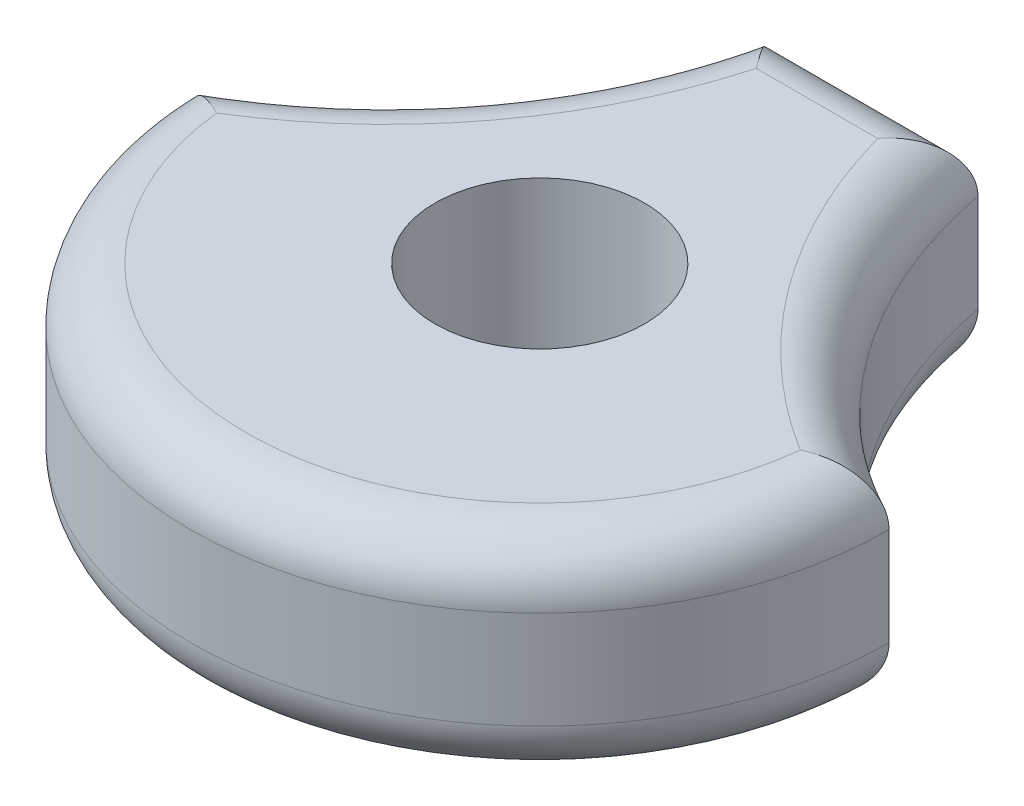
SolidWorks part; units mm, degrees
ref_plane "Front Plane" through (0, 0, 0) normal (0, 0, 1) x (1, 0, 0)
ref_plane "Top Plane" through (0, 0, 0) normal (0, 1, 0) x (1, 0, 0)
ref_plane "Right Plane" through (0, 0, 0) normal (1, 0, 0) x (0, 0, -1)
sketch "Sketch1" plane through (0, 0, 0) normal (0, 1, 0) x (1, 0, 0)
  line L1 (-0.188, 0.5961) -> (0.188, 0.5961)
  arc A0 (-0.625, 0) -> (0.625, 0) centre (0, 0) ccw
  arc A3 (-0.625, 0) -> (-0.188, 0.5961) centre (-1.0238, 0.7506) ccw
  arc A4 (0.188, 0.5961) -> (0.625, 0) centre (1.0238, 0.7506) ccw
  point P1 (0, 0)
  point P8 (0, 0)
  point P13 (0, 0)
  point P14 (-1.0193, 0.7513)
  point P15 (-1.6845, 0.7083)
  point P16 (0, 0)
  point P17 (0, 0)
  point P18 (0, 0)
  point P19 (1.0238, 0.7506)
  dimension "D1" = 1.25
  dimension "D3" = 0.376
extrude "Boss-Extrude1" add sketch "Sketch1" along normal blind 0.375
sketch "Sketch2" plane through (0, 0.375, 0) normal (0, 1, 0) x (1, 0, 0)
  circle A0 centre (0, 0) radius 0.1875
  dimension "D1" = 0.375
extrude "Cut-Extrude1" cut sketch "Sketch2" against normal blind 0.375
fillet "Fillet2" radius 0.1 8 edges at (0, 0, 0.625) (0.3383, 0, -0.248) (0, 0, -0.5961) (-0.3383, 0, -0.248) (-0.3383, 0.375, -0.248) (0, 0.375, -0.5961) (0.3383, 0.375, -0.248) (0, 0.375, 0.625)
sketch "Sketch4" plane through (0, 0, 0) normal (0, -1, 0) x (1, 0, 0)
  circle A0 centre (0, -0.375) radius 0.0935
  point P5 (0, 0)
  point P7 (0, 0)
  point P8 (0, 0)
  dimension "D1" = 0.187
  dimension "D2" = 0.188
  dimension "D3" = 0.375
extrude "Cut-Extrude2" cut sketch "Sketch4" against normal blind 0.187
